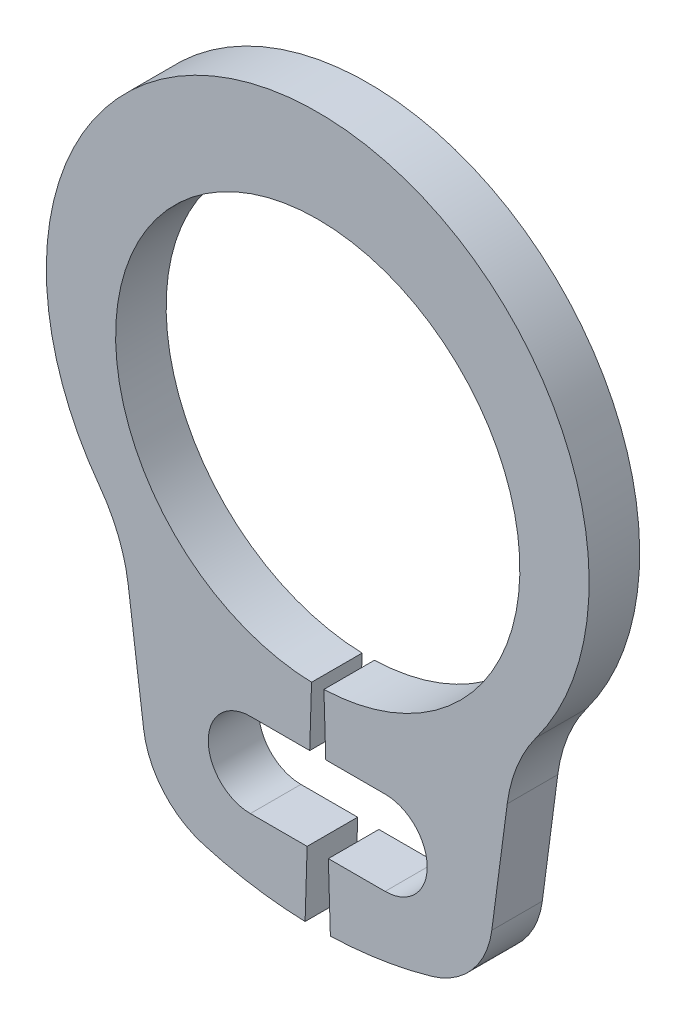
SolidWorks part; units mm, degrees
ref_plane "Plane1" through (0, 0, 0) normal (0, 0, 1) x (1, 0, 0)
ref_plane "Plane2" through (0, 0, 0) normal (0, 1, 0) x (1, 0, 0)
ref_plane "Plane3" through (0, 0, 0) normal (1, 0, 0) x (0, 0, -1)
sketch "Clipboard" plane through (0, 0, 0) normal (0, 0, 1) x (1, 0, 0)
  line L0 (0, 0) -> (1.1, 0)
  line L1 (0, 0) -> (0, 0.66)
  line L2 (0, 0) -> (0, -2.5)
  circle A0 centre (0, 0) radius 0.5
  circle A1 centre (0, 0) radius 2.5
  dimension "HoleDia" = 1
  dimension "ShaftDia" = 5
  dimension "LargeSection" = 1.1
  dimension "SmallSection" = 0.66
  dimension "LugSection" = 2.5
sketch "BodySke" plane through (0, 0, 0) normal (0, 0, 1) x (1, 0, 0)
  line L0 (-1.5431, 0) -> (1.5431, 0) construction
  line L1 (0, 0) -> (0, 3.5) construction
  line L2 (0.0735, -2.3989) -> (0.15, -4.8977)
  line L3 (-0.0735, -2.3989) -> (-0.15, -4.8977)
  line L4 (0, 0) -> (4.0714, -2.7265) construction
  line L5 (0, 0) -> (-4.0714, -2.7265) construction
  line L7 (2.2501, -2.4867) -> (2.0668, -3.8794)
  line L8 (-2.2501, -2.4867) -> (-2.0668, -3.8794)
  circle A0 centre (0, 0) radius 2.4 construction
  arc A1 (0.0735, -2.3989) -> (-0.0735, -2.3989) centre (0, 0) ccw
  arc A2 (2.5425, -1.7027) -> (-2.5425, -1.7027) centre (0, 0.2774) ccw construction
  arc A3 (0.15, -4.8977) -> (1.351, -4.7101) centre (0, 0) ccw
  arc A4 (2.5932, -1.6359) -> (2.2501, -2.4867) centre (4.0714, -2.7265) ccw
  arc A5 (-2.2501, -2.4867) -> (-2.5932, -1.6359) centre (-4.0714, -2.7265) ccw
  arc A6 (-1.351, -4.7101) -> (-0.15, -4.8977) centre (0, 0) ccw
  arc A7 (2.5932, -1.6359) -> (-2.5932, -1.6359) centre (0, 0.2774) ccw
  arc A8 (-2.1843, -2.9864) -> (2.1843, -2.9864) centre (0, 0) ccw construction
  circle A9 centre (0.8, -3.6125) radius 0.5
  circle A10 centre (-0.8, -3.6125) radius 0.5
  arc A11 (2.0668, -3.8794) -> (1.351, -4.7101) centre (1.0753, -3.7488) cw
  arc A12 (-2.0668, -3.8794) -> (-1.351, -4.7101) centre (-1.0753, -3.7488) ccw
  point P28 (1.9879, -4.4787)
  point P31 (-1.9879, -4.4787)
  dimension "GrooveDia" = 4.8
  dimension "D3" = 1
  dimension "LugRad" = 4.9
  dimension "HoleOffsetRad" = 3.7
  dimension "HoleDia" = 1
  dimension "D2" = 15
  dimension "LargeRad" = 3.5
  dimension "SmallRad" = 3.06
  dimension "Gap" = 0.3
  dimension "SmallAngle" = 112.382
  dimension "HoleSpacing" = 1.6
extrude "Body" add sketch "BodySke" against normal blind 0.6
sketch "NotSke" plane through (0, 0, 0) normal (0, 0, 1) x (1, 0, 0)
  line L0 (0.8, -3.1125) -> (0.8, -4.1125)
  line L1 (0.8, -4.1125) -> (-0.8, -4.1125)
  line L2 (-0.8, -4.1125) -> (-0.8, -3.1125)
  line L3 (-0.8, -3.1125) -> (0.8, -3.1125)
  circle A0 centre (0.8, -3.6125) radius 0.5 construction
  circle A1 centre (-0.8, -3.6125) radius 0.5 construction
extrude "Notch" cut sketch "NotSke" against normal through all
sketch "UnlSke" plane through (0, 0, 0) normal (0, 0, 1) x (1, 0, 0)
  line L0 (1.351, -1.9836) -> (1.351, -4.7101)
  line L1 (-1.351, -1.9836) -> (-1.351, -4.7101)
  arc A0 (1.351, -1.9836) -> (-1.351, -1.9836) centre (0, 0) ccw
  arc A1 (1.351, -4.7101) -> (-1.351, -4.7101) centre (0, 0) ccw
  arc A4 (-1.351, -4.7101) -> (-0.15, -4.8977) centre (0, 0) ccw construction
  arc A5 (0.0735, -2.3989) -> (-0.0735, -2.3989) centre (0, 0) ccw construction
extrude "Unlug" [suppressed] add sketch "UnlSke" against normal through all
equation "' \"ShaftDia@Clipboard\" = 3"
equation "' \"Thickness@Body\" = 0.4"
equation "' \"GrooveDia@BodySke\" = 2.8"
equation "' \"LugSection@Clipboard\" = 1.9"
equation "' \"LargeSection@Clipboard\" = 0.8"
equation "' \"HoleDia@Clipboard\" = 0.8"
equation "' \"ShaftDia@Clipboard\" = 9"
equation "' \"Thickness@Body\" = 1"
equation "' \"GrooveDia@BodySke\" = 8.6"
equation "' \"LugSection@Clipboard\" = 3.3"
equation "' \"LargeSection@Clipboard\" = 1.7"
equation "' \"HoleDia@Clipboard\" = 1.2"
equation "\"SmallSection@Clipboard\" =  \"LargeSection@Clipboard\" * 0.6"
equation "\"Gap@BodySke\" =  \"Thickness@Body\" / 2"
equation "\"LargeRad@BodySke\" =  \"GrooveDia@BodySke\" / 2 +  \"LargeSection@Clipboard\""
equation "\"SmallRad@BodySke\" =  \"GrooveDia@BodySke\" / 2 +  \"SmallSection@Clipboard\""
equation "\"LugRad@BodySke\" = \"GrooveDia@BodySke\" / 2 + \"LugSection@Clipboard\""
equation "\"HoleOffsetRad@BodySke\" = (  \"ShaftDia@Clipboard\" / 2 + \"LugRad@BodySke\" ) / 2"
equation "\"HoleSpacing@BodySke\" = \"Gap@BodySke\"  * 2 +  \"HoleDia@Clipboard\""
equation "\"HoleDia@BodySke\" =  \"HoleDia@Clipboard\""
equation "\"SmallAngle@BodySke\" = atn(\"HoleSpacing@BodySke\" / 2 / sqr(\"HoleOffsetRad@BodySke\"  * \"HoleOffsetRad@BodySke\" - (\"HoleSpacing@BodySke\" / 2) * (\"HoleSpacing@BodySke\" / 2) ))  * 9 * ( 180 / 3.141593)"
